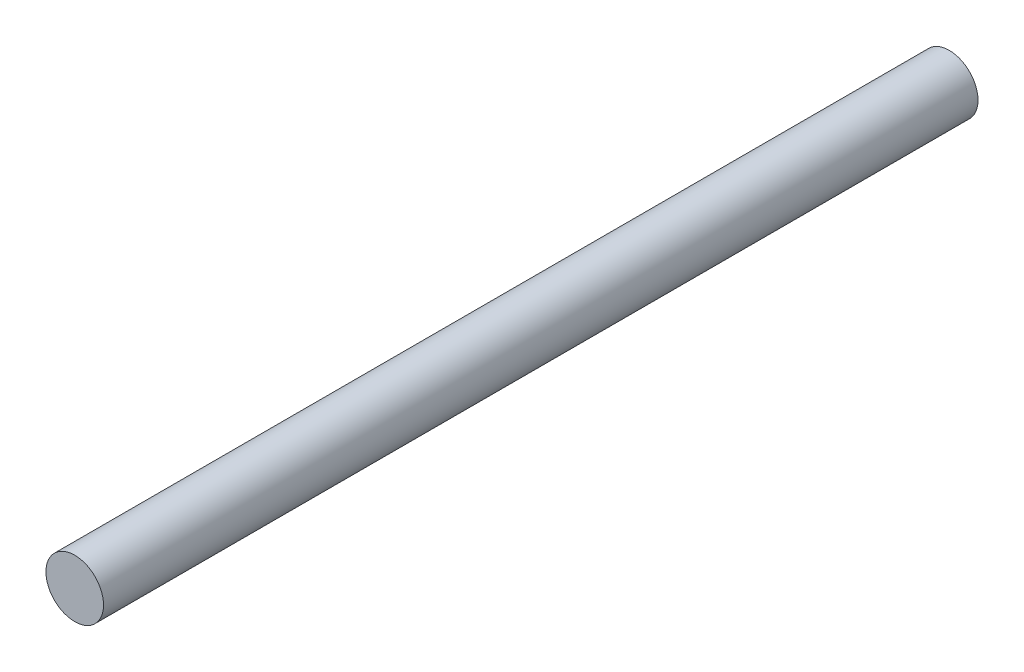
SolidWorks part; units mm, degrees
ref_plane "Спереди" through (0, 0, 0) normal (0, 0, 1) x (1, 0, 0)
ref_plane "Сверху" through (0, 0, 0) normal (0, 1, 0) x (1, 0, 0)
ref_plane "Справа" through (0, 0, 0) normal (1, 0, 0) x (0, 0, -1)
sketch "Эскиз1" plane through (0, 0, 0) normal (0, 0, 1) x (1, 0, 0)
  circle A0 centre (0, 0) radius 3.95
extrude "Бобышка-Вытянуть1" add sketch "Эскиз1" along normal blind 120
